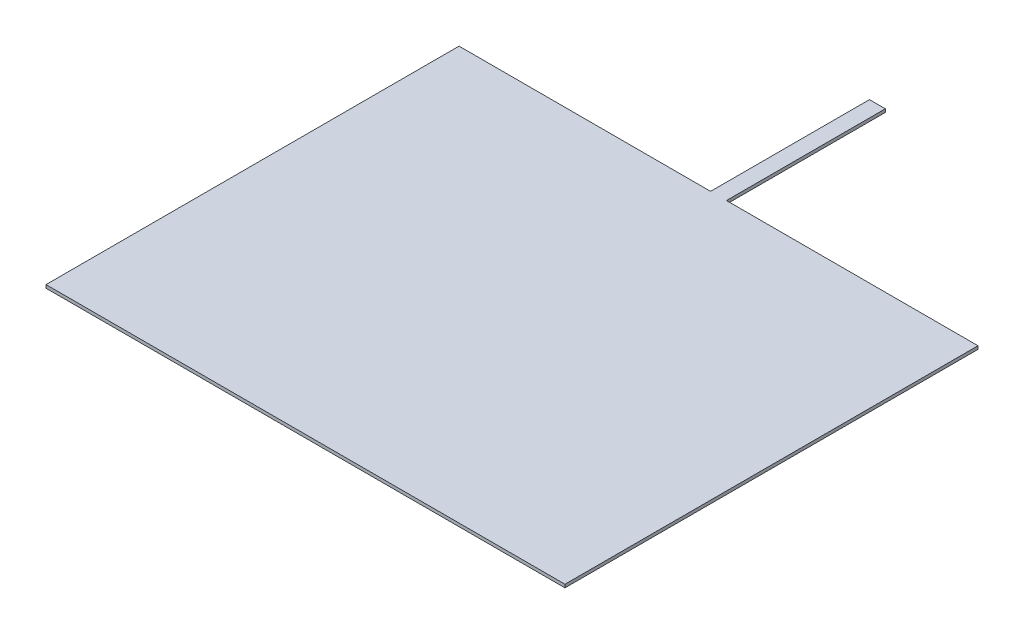
SolidWorks part; units mm, degrees
ref_plane "Спереди" through (0, 0, 0) normal (0, 0, 1) x (1, 0, 0)
ref_plane "Сверху" through (0, 0, 0) normal (0, 1, 0) x (1, 0, 0)
ref_plane "Справа" through (0, 0, 0) normal (1, 0, 0) x (0, 0, -1)
other "Configuration Table"
sketch "Эскиз1" plane through (0, 0, 0) normal (0, 1, 0) x (1, 0, 0)
  line L1 (0, 0) -> (98, 0)
  line L2 (0, 0) -> (0, 78)
  line L3 (0, 78) -> (98, 78)
  line L4 (98, 0) -> (98, 78)
  line L5 (47.5, 48) -> (50.5, 48)
  line L6 (47.5, 48) -> (47.5, 108)
  line L7 (47.5, 108) -> (50.5, 108)
  line L8 (50.5, 48) -> (50.5, 108)
  line L9 (47.5, 48) -> (50.5, 108) construction
  line L10 (47.5, 108) -> (50.5, 48) construction
  point P5 (49, 78)
  point P6 (49, 78)
  point P11 (0, 0)
  point P12 (0, 0)
extrude "Бобышка-Вытянуть1" add sketch "Эскиз1" along normal blind 0.6 contours L8 L5 L6 L3 L2 L1 L4 | L3 L8 L7 L6 | L5 L8 L3 L6
